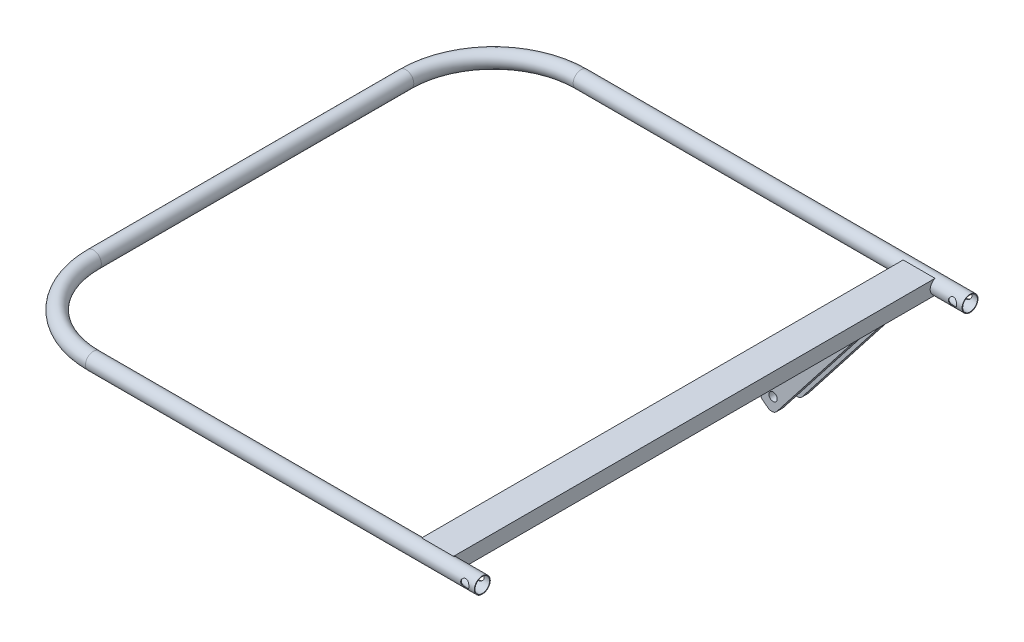
SolidWorks part; units mm, degrees
ref_plane "Front Plane" through (0, 0, 0) normal (0, 0, 1) x (1, 0, 0)
ref_plane "Top Plane" through (0, 0, 0) normal (0, 1, 0) x (1, 0, 0)
ref_plane "Right Plane" through (0, 0, 0) normal (1, 0, 0) x (0, 0, -1)
sketch "Sketch1" plane through (0, 0, 0) normal (0, 1, 0) x (1, 0, 0)
  line L0 (0, 395) -> (-610, 395)
  line L1 (-760, 245) -> (-760, -245)
  line L2 (-610, -395) -> (0, -395)
  line L3 (-917.8851, 0) -> (889.0078, 0) construction
  arc A0 (-610, -395) -> (-760, -245) centre (-610, -245) cw
  arc A1 (-760, 245) -> (-610, 395) centre (-610, 245) cw
  point P9 (-760, -395)
  point P12 (-760, 395)
  dimension "D3" = 150
  dimension "D1" = 790
  dimension "D2" = 760
ref_plane "Plane1" through (0, 0, 395) normal (1, 0, 0) x (0, 0, -1)
sketch "Sketch2" plane through (0, 0, 395) normal (1, 0, 0) x (0, 0, -1)
  line L0 (150, 0) -> (0, 0) construction
  circle A0 centre (12.5, 0) radius 12.5
  dimension "D1" = 25
sweep "Sweep-Thin1" add profiles "Sketch2" path "Sketch1" parameters "D1"=1
ref_plane "Plane2" through (0, 12.5, 0) normal (0, 1, 0) x (1, 0, 0)
sketch "Sketch3" plane through (0, 12.5, 0) normal (0, 1, 0) x (1, 0, 0)
  line L0 (-747.5, -245) -> (-747.5, 245)
  line L1 (-735, -245) -> (-760, -245) construction
  line L2 (-735, 245) -> (-760, 245) construction
  line L3 (-747.5, 245) -> (-610, 382.5)
  line L4 (-610, 370) -> (-610, 395) construction
  line L5 (-610, 382.5) -> (-127.5, 382.5)
  line L6 (-127.5, 382.5) -> (-127.5, -382.5)
  line L7 (-127.5, -382.5) -> (-610, -382.5)
  line L8 (-610, -370) -> (-610, -395) construction
  line L9 (-610, -382.5) -> (-747.5, -245)
  dimension "D1" = 620
sketch "Sketch14" plane through (0, 0, 0) normal (0, 0, 1) x (1, 0, 0)
  line L0 (0, 0) -> (-219.6707, 0) construction
  line L1 (0, 11.5) -> (-610, 11.5) construction
  line L2 (-100, -11.5) -> (-50, -11.5)
  line L3 (-100, -11.5) -> (-100, 11.5)
  line L4 (-100, 11.5) -> (-50, 11.5)
  line L5 (-50, -11.5) -> (-50, 11.5)
  line L6 (-100, -11.5) -> (-50, 11.5) construction
  line L7 (-100, 11.5) -> (-50, -11.5) construction
  circle A0 centre (-747.5, 0) radius 12.5 construction
  point P3 (-75, 0)
  dimension "D1" = 697.5
  dimension "D2" = 50
extrude "Boss-Extrude1" add sketch "Sketch14" along normal mid plane 763
sketch "Sketch15" plane through (0, 0, 0) normal (0, 0, 1) x (1, 0, 0)
  line L0 (0, 0) -> (-193.1237, 0) construction
  circle A0 centre (-15, 0) radius 6.5
  dimension "D2" = 13
  dimension "D1" = 15
extrude "Cut-Extrude1" cut sketch "Sketch15" against normal mid plane 873
sketch "Sketch16" plane through (0, -11.5, 0) normal (0, -1, 0) x (1, 0, 0)
  line L1 (-95, -357.601) -> (-55, -357.601)
  line L2 (-95, -357.601) -> (-95, -257.601)
  line L3 (-95, -257.601) -> (-55, -257.601)
  line L4 (-55, -357.601) -> (-55, -257.601)
  line L5 (-75, -377.601) -> (-75, -210.482) construction
  line L6 (-50, -377.601) -> (-100, -377.601) construction
  point P8 (-75, -357.601)
  dimension "D1" = 100
  dimension "D2" = 40
  dimension "D3" = 20
extrude "Boss-Extrude2" add sketch "Sketch16" along normal blind 5
ref_plane "Plane3" through (0, 0, -302.601) normal (0, 0, -1) x (-1, 0, 0)
sketch "Sketch17" plane through (0, 0, -302.601) normal (0, 0, -1) x (-1, 0, 0)
  line L0 (95, -16.5) -> (55, -16.5) construction
  line L1 (75, -16.5) -> (75, -41.8835) construction
  line B0 (90, -16.5) -> (60, -16.5)
  line B1 (60, -16.5) -> (198.241, -193.4777)
  line B2 (212.2776, -195.2026) -> (220.4261, -188.8377)
  line B3 (221.9467, -174.5482) -> (90, -16.5)
  line B4 (216.3518, -192.0201) -> (154.6547, -113.0348) construction
  arc B5 (198.241, -193.4777) -> (212.2776, -195.2026) centre (206.1218, -187.3219) ccw
  arc B6 (220.4261, -188.8377) -> (221.9467, -174.5482) centre (214.2703, -180.9569) ccw
  circle B7 centre (204.0402, -176.2587) radius 6.5
sketch_block_instance "Block-Sketch22-3"
sketch_block "Block-Sketch22" parameters "D1"=30, "D2"=300
sketch_block_instance "Block1-2"
sketch_block "Block1" parameters "D2"=10, "D4"=13, "D1"=30, "D3"=20, "D5"=170.7926
ref_plane "Plane4" through (0, 0, -317.601) normal (0, 0, -1) x (-1, 0, 0)
sketch "Sketch18" plane through (0, 0, -317.601) normal (0, 0, -1) x (-1, 0, 0)
  line L0 (90, -16.5) -> (60, -16.5) construction
  line L1 (212.2776, -195.2026) -> (220.4261, -188.8377) construction
  line L2 (221.9467, -174.5482) -> (90, -16.5) construction
  line L3 (60, -16.5) -> (198.241, -193.4777) construction
  line L4 (90, -16.5) -> (60, -16.5)
  line L5 (212.2776, -195.2026) -> (220.4261, -188.8377)
  line L6 (221.9467, -174.5482) -> (90, -16.5)
  line L7 (60, -16.5) -> (198.241, -193.4777)
  circle A0 centre (204.0402, -176.2587) radius 6.5 construction
  arc A1 (198.241, -193.4777) -> (212.2776, -195.2026) centre (206.1218, -187.3219) ccw construction
  arc A2 (220.4261, -188.8377) -> (221.9467, -174.5482) centre (214.2703, -180.9569) ccw construction
  circle A3 centre (204.0402, -176.2587) radius 6.5
  arc A4 (198.241, -193.4777) -> (212.2776, -195.2026) centre (206.1218, -187.3219) ccw
  arc A5 (220.4261, -188.8377) -> (221.9467, -174.5482) centre (214.2703, -180.9569) ccw
extrude "Boss-Extrude3" add sketch "Sketch18" along normal blind 10
mirror "Mirror1" about plane through (0, 0, -302.601) normal (0, 0, -1) of "Boss-Extrude3"
sketch "Bend-Lines1" [suppressed] plane through (0, 0, 0) normal (0, 1, 0) x (1, 0, 0)
sketch "Bounding-Box1" [suppressed] plane through (0, 0, 0) normal (0, 1, 0) x (1, 0, 0)
